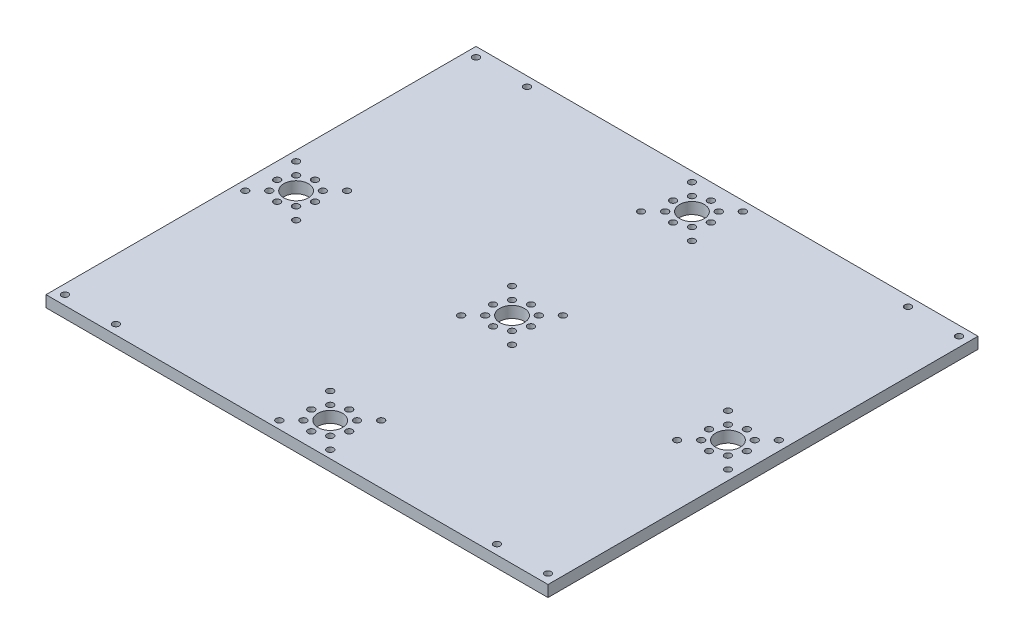
SolidWorks part; units mm, degrees
ref_plane "Plan de face" through (0, 0, 0) normal (0, 0, 1) x (1, 0, 0)
ref_plane "Plan de dessus" through (0, 0, 0) normal (0, 1, 0) x (1, 0, 0)
ref_plane "Plan de droite" through (0, 0, 0) normal (1, 0, 0) x (0, 0, -1)
sketch "Esquisse1" plane through (0, 0, 0) normal (0, 1, 0) x (1, 0, 0)
  line L0 (0, 0) -> (265, 0)
  line L1 (0, 0) -> (0, -227)
  line L2 (0, -227) -> (265, -227)
  line L3 (265, -227) -> (265, 0)
  line L7 (37, -35.0701) -> (228, -35.0701)
  line L8 (228, -35.0701) -> (228, -191.9299)
  line L9 (228, -191.9299) -> (37, -191.9299)
  line L10 (37, -191.9299) -> (37, -35.0701)
  line L19 (238, -98) -> (255, -98)
  line L22 (238, -18) -> (238, -98)
  line L23 (238, -18) -> (255, -18)
  line L24 (255, -18) -> (255, -98)
  line L29 (238, -209) -> (238, -129)
  line L30 (238, -209) -> (255, -209)
  line L31 (255, -209) -> (255, -129)
  line L32 (238, -129) -> (255, -129)
  line L33 (27, -18) -> (27, -98)
  line L34 (27, -18) -> (10, -18)
  line L35 (10, -18) -> (10, -98)
  line L36 (27, -98) -> (10, -98)
  line L37 (27, -209) -> (10, -209)
  line L38 (10, -209) -> (10, -129)
  line L39 (27, -129) -> (10, -129)
  line L40 (27, -209) -> (27, -129)
  circle A0 centre (246.5, -113.5) radius 6.5
  circle A1 centre (246.5, -103.5) radius 1.75
  circle A2 centre (253.5711, -106.4289) radius 1.75
  circle A3 centre (256.5, -113.5) radius 1.75
  circle A4 centre (253.5711, -120.5711) radius 1.75
  circle A5 centre (246.5, -123.5) radius 1.75
  circle A6 centre (239.4289, -120.5711) radius 1.75
  circle A7 centre (236.5, -113.5) radius 1.75
  circle A8 centre (239.4289, -106.4289) radius 1.75
  circle A9 centre (259.935, -100.065) radius 1.75
  circle A10 centre (259.935, -126.935) radius 1.75
  circle A11 centre (233.065, -100.065) radius 1.75
  circle A12 centre (233.065, -126.935) radius 1.75
  circle A13 centre (132.5, -209.465) radius 6.5
  circle A14 centre (132.5, -199.465) radius 1.75
  circle A15 centre (139.5711, -202.3939) radius 1.75
  circle A16 centre (142.5, -209.465) radius 1.75
  circle A17 centre (139.5711, -216.536) radius 1.75
  circle A18 centre (132.5, -219.465) radius 1.75
  circle A19 centre (125.4289, -216.536) radius 1.75
  circle A20 centre (122.5, -209.465) radius 1.75
  circle A21 centre (125.4289, -202.3939) radius 1.75
  circle A22 centre (145.935, -196.0299) radius 1.75
  circle A23 centre (145.935, -222.9) radius 1.75
  circle A24 centre (119.065, -196.0299) radius 1.75
  circle A25 centre (119.065, -222.9) radius 1.75
  circle A26 centre (18.514, -113.5) radius 6.5
  circle A27 centre (18.514, -103.5) radius 1.75
  circle A28 centre (25.585, -106.4289) radius 1.75
  circle A29 centre (28.514, -113.5) radius 1.75
  circle A30 centre (25.585, -120.5711) radius 1.75
  circle A31 centre (18.514, -123.5) radius 1.75
  circle A32 centre (11.4429, -120.5711) radius 1.75
  circle A33 centre (8.514, -113.5) radius 1.75
  circle A34 centre (11.4429, -106.4289) radius 1.75
  circle A35 centre (31.949, -100.065) radius 1.75
  circle A36 centre (31.949, -126.935) radius 1.75
  circle A37 centre (5.0789, -100.065) radius 1.75
  circle A38 centre (5.0789, -126.935) radius 1.75
  circle A39 centre (132.5, -18.5) radius 6.5
  circle A40 centre (132.5, -8.5) radius 1.75
  circle A41 centre (139.5711, -11.4289) radius 1.75
  circle A42 centre (142.5, -18.5) radius 1.75
  circle A43 centre (139.5711, -25.5711) radius 1.75
  circle A44 centre (132.5, -28.5) radius 1.75
  circle A45 centre (125.4289, -25.5711) radius 1.75
  circle A46 centre (122.5, -18.5) radius 1.75
  circle A47 centre (125.4289, -11.4289) radius 1.75
  circle A48 centre (145.935, -5.065) radius 1.75
  circle A49 centre (145.935, -31.935) radius 1.75
  circle A50 centre (119.065, -5.065) radius 1.75
  circle A51 centre (119.065, -31.935) radius 1.75
  circle A52 centre (260, -5) radius 1.75
  circle A53 centre (233.065, -5) radius 1.75
  circle A60 centre (260, -222) radius 1.75
  circle A61 centre (233.065, -222) radius 1.75
  circle A62 centre (5, -5) radius 1.75
  circle A63 centre (31.935, -5) radius 1.75
  circle A64 centre (5, -222) radius 1.75
  circle A65 centre (31.935, -222) radius 1.75
  dimension "D1" = 265
  dimension "D2" = 227
  dimension "D3" = 227
extrude "Boss.-Extru.1" add sketch "Esquisse1" along normal blind 6
sketch "Esquisse2" plane through (0, 6, 0) normal (0, 1, 0) x (1, 0, 0)
  line L1 (10, -18) -> (27, -18)
  line L2 (10, -18) -> (10, -98)
  line L3 (10, -98) -> (27, -98)
  line L4 (27, -18) -> (27, -98)
  line L5 (37, -35.0701) -> (228, -35.0701)
  line L6 (37, -35.0701) -> (37, -191.9299)
  line L7 (37, -191.9299) -> (228, -191.9299)
  line L8 (228, -35.0701) -> (228, -191.9299)
  line L9 (238, -18) -> (255, -18)
  line L10 (238, -18) -> (238, -98)
  line L11 (238, -98) -> (255, -98)
  line L12 (255, -18) -> (255, -98)
  line L13 (238, -129) -> (255, -129)
  line L14 (238, -129) -> (238, -209)
  line L15 (238, -209) -> (255, -209)
  line L16 (255, -129) -> (255, -209)
  line L17 (10, -209) -> (27, -209)
  line L18 (10, -209) -> (10, -129)
  line L19 (10, -129) -> (27, -129)
  line L20 (27, -209) -> (27, -129)
  circle A0 centre (132.5, -113.5) radius 6.5
  circle A1 centre (132.5, -103.5) radius 1.75
  circle A2 centre (139.5711, -106.4289) radius 1.75
  circle A3 centre (142.5, -113.5) radius 1.75
  circle A4 centre (139.5711, -120.5711) radius 1.75
  circle A5 centre (132.5, -123.5) radius 1.75
  circle A6 centre (125.4289, -120.5711) radius 1.75
  circle A7 centre (122.5, -113.5) radius 1.75
  circle A8 centre (125.4289, -106.4289) radius 1.75
  circle A9 centre (145.935, -100.065) radius 1.75
  circle A10 centre (145.935, -126.935) radius 1.75
  circle A11 centre (119.065, -100.065) radius 1.75
  circle A12 centre (119.065, -126.935) radius 1.75
extrude "Boss.-Extru.3" add sketch "Esquisse2" against normal blind 6
